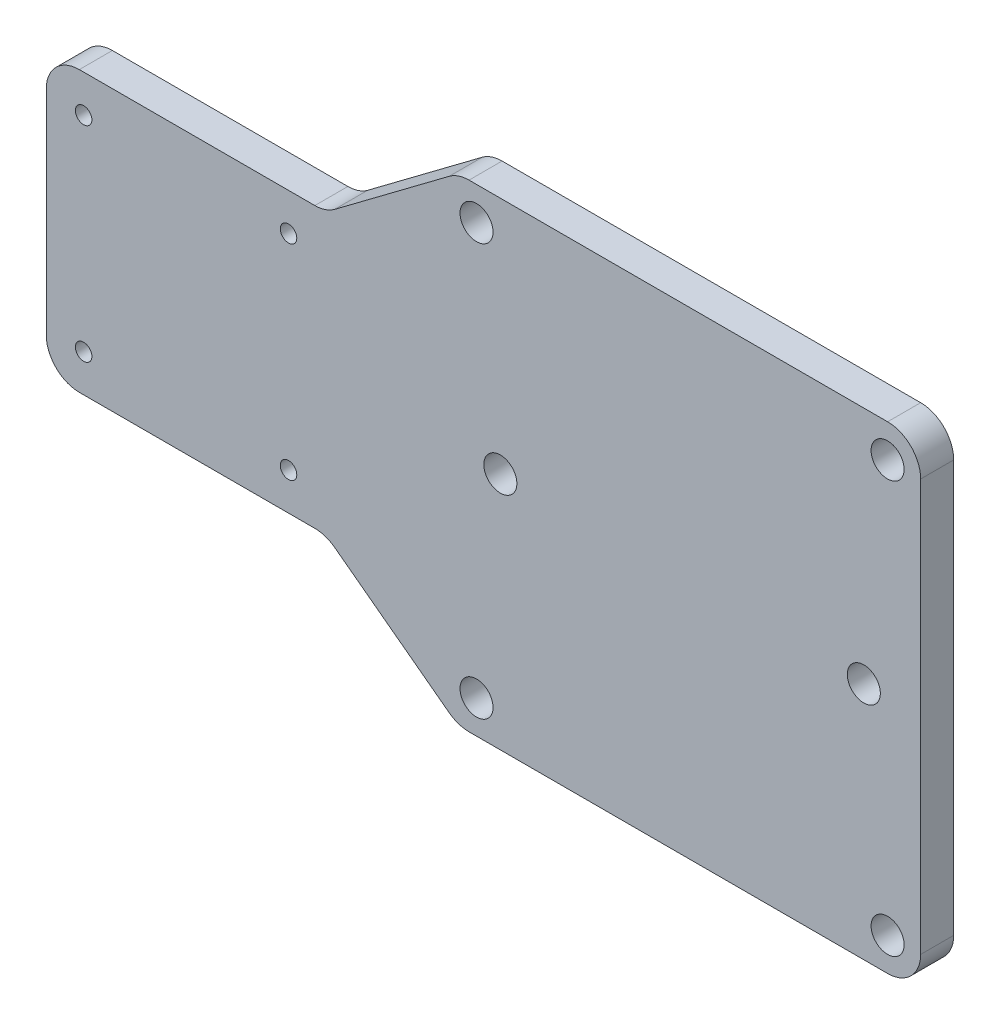
SolidWorks part; units mm, degrees
ref_plane "Front Plane" through (0, 0, 0) normal (0, 0, 1) x (1, 0, 0)
ref_plane "Top Plane" through (0, 0, 0) normal (0, 1, 0) x (1, 0, 0)
ref_plane "Right Plane" through (0, 0, 0) normal (1, 0, 0) x (0, 0, -1)
sketch "Sketch1" plane through (0, 0, 0) normal (0, 0, 1) x (1, 0, 0)
  line L0 (21.15, 21.15) -> (41.15, 36.15)
  line L1 (-21.15, -21.15) -> (21.15, -21.15)
  line L2 (-21.15, -21.15) -> (-21.15, 21.15)
  line L3 (-21.15, 21.15) -> (21.15, 21.15)
  line L5 (-21.15, -21.15) -> (21.15, 21.15) construction
  line L6 (-21.15, 21.15) -> (21.15, -21.15) construction
  line L7 (41.15, 36.15) -> (111.15, 36.15)
  line L9 (41.15, -36.15) -> (111.15, -36.15)
  line L10 (111.15, 36.15) -> (111.15, -36.15)
  line L11 (21.15, -21.15) -> (41.15, -36.15)
  point P0 (0, 0)
  dimension "D1" = 42.3
  dimension "D2" = 42.3
  dimension "D3" = 72.3
  dimension "D4" = 70
  dimension "D5" = 15
  dimension "D6" = 42.3
  dimension "D7" = 70
  dimension "D8" = 20
extrude "Boss-Extrude1" add sketch "Sketch1" along normal blind 5
fillet "Fillet2" radius 5 1 edges at (-21.15, -21.15, 2.5)
fillet "Fillet3" radius 5 1 edges at (-21.15, 21.15, 2.5)
fillet "Fillet4" radius 5 1 edges at (21.15, 21.15, 2.5)
fillet "Fillet5" radius 5 1 edges at (21.15, -21.15, 2.5)
fillet "Fillet6" radius 5 1 edges at (41.15, -36.15, 2.5)
fillet "Fillet7" radius 5 1 edges at (41.15, 36.15, 2.5)
fillet "Fillet8" radius 5 1 edges at (111.15, 36.15, 2.5)
fillet "Fillet9" radius 5 1 edges at (111.15, -36.15, 2.5)
sketch "Sketch2" plane through (0, 0, 5) normal (0, 0, 1) x (1, 0, 0)
  line L0 (-16.15, -21.15) -> (19.4833, -21.15) construction
  line L1 (-21.15, 16.15) -> (-21.15, -16.15) construction
  line L2 (19.4833, 21.15) -> (-16.15, 21.15) construction
  line L3 (106.15, 36.15) -> (42.8167, 36.15) construction
  line L8 (42.8167, -36.15) -> (106.15, -36.15) construction
  line L9 (111.15, -31.15) -> (111.15, 31.15) construction
  circle A0 centre (-15.5, -15.5) radius 1.25
  circle A1 centre (-15.5, 15.5) radius 1.25
  circle A2 centre (15.5, 15.5) radius 1.25
  circle A3 centre (15.5, -15.5) radius 1.25
  circle A4 centre (106.15, 31.15) radius 2.5
  circle A5 centre (106.15, -31.15) radius 2.5
  circle A6 centre (43.95, -31.15) radius 2.5
  circle A7 centre (43.95, 31.15) radius 2.5
  circle A8 centre (102.55, 0) radius 2.5
  circle A9 centre (47.55, 0) radius 2.5
  dimension "D1" = 2.5
  dimension "D4" = 2.5
  dimension "D7" = 2.5
  dimension "D8" = 2.5
  dimension "D11" = 5
  dimension "D12" = 5
  dimension "D13" = 5
  dimension "D14" = 5
  dimension "D21" = 5
  dimension "D23" = 5
  dimension "D2" = 5.65
  dimension "D3" = 5.65
  dimension "D5" = 5.65
  dimension "D6" = 5.65
  dimension "D9" = 31
  dimension "D10" = 31
  dimension "D15" = 62.2
  dimension "D16" = 5
  dimension "D17" = 5
  dimension "D18" = 5
  dimension "D19" = 62.2
  dimension "D20" = 5
  dimension "D22" = 5
  dimension "D24" = 55
  dimension "D26" = 5
  dimension "D27" = 3.6
extrude "Cut-Extrude1" cut sketch "Sketch2" against normal blind 10
